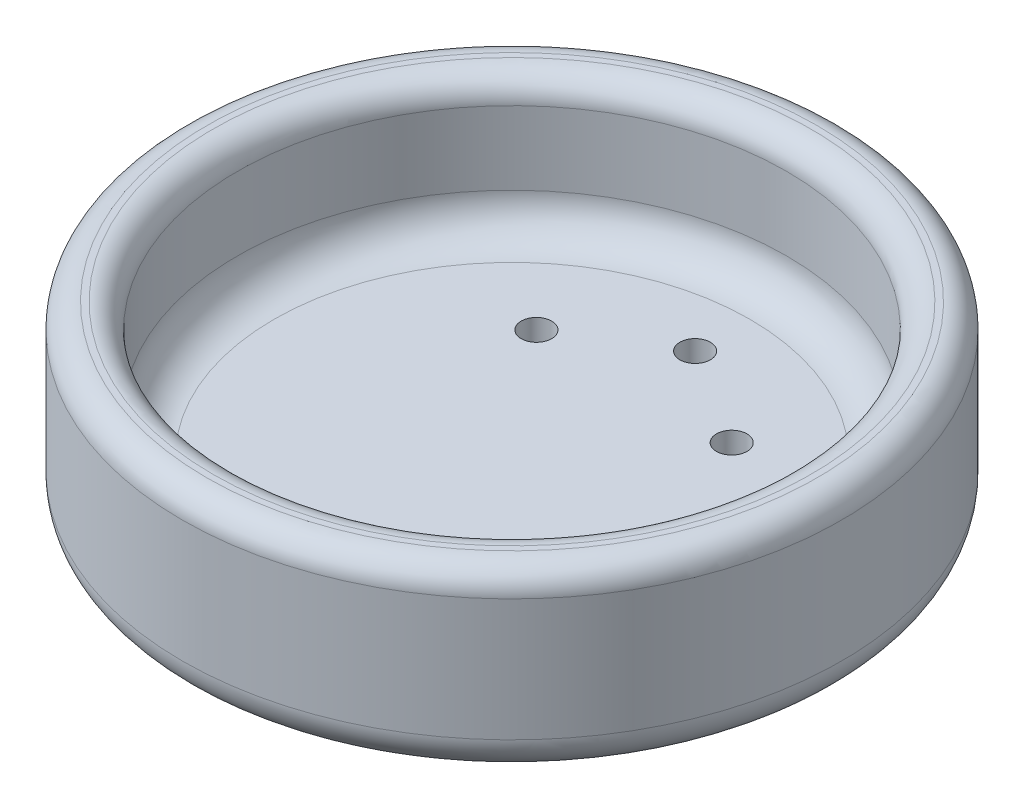
SolidWorks part; units mm, degrees
ref_plane "Front" through (0, 0, 0) normal (0, 0, 1) x (1, 0, 0)
ref_plane "Top" through (0, 0, 0) normal (0, 1, 0) x (1, 0, 0)
ref_plane "Right" through (0, 0, 0) normal (1, 0, 0) x (0, 0, -1)
sketch "Sketch1" plane through (0, 0, 0) normal (0, 1, 0) x (1, 0, 0)
  circle A0 centre (0, 0) radius 27
  dimension "D1" = 54
extrude "Boss-Extrude1" add sketch "Sketch1" along normal blind 15 contours A0
sketch "Sketch2" plane through (0, 15, 0) normal (0, 1, 0) x (1, 0, 0)
  circle A0 centre (0, 0) radius 22.5
  dimension "D1" = 45
extrude "Cut-Extrude1" cut sketch "Sketch2" against normal blind 11 contours A0
fillet "Fillet1" radius 3 1 edges at (0, 0, 27)
fillet "Fillet2" radius 3 1 edges at (0, 4, 22.5)
fillet "Fillet3" radius 2 1 edges at (0, 15, 27)
fillet "Fillet4" radius 2 1 edges at (0, 15, 22.5)
sketch "Sketch4" plane through (0, 4, 0) normal (0, 1, 0) x (1, 0, 0)
  line L0 (0, 15) -> (0, 0) construction
  line L1 (-8, 10) -> (8, 10) construction
  circle A0 centre (-8, 10) radius 1.25
  circle A1 centre (8, 10) radius 1.25
  circle A2 centre (0, 15) radius 1.25
  dimension "D2" = 2.5
  dimension "D1" = 16
  dimension "D3" = 5
  dimension "D4" = 10
extrude "Cut-Extrude2" cut sketch "Sketch4" against normal blind 11
